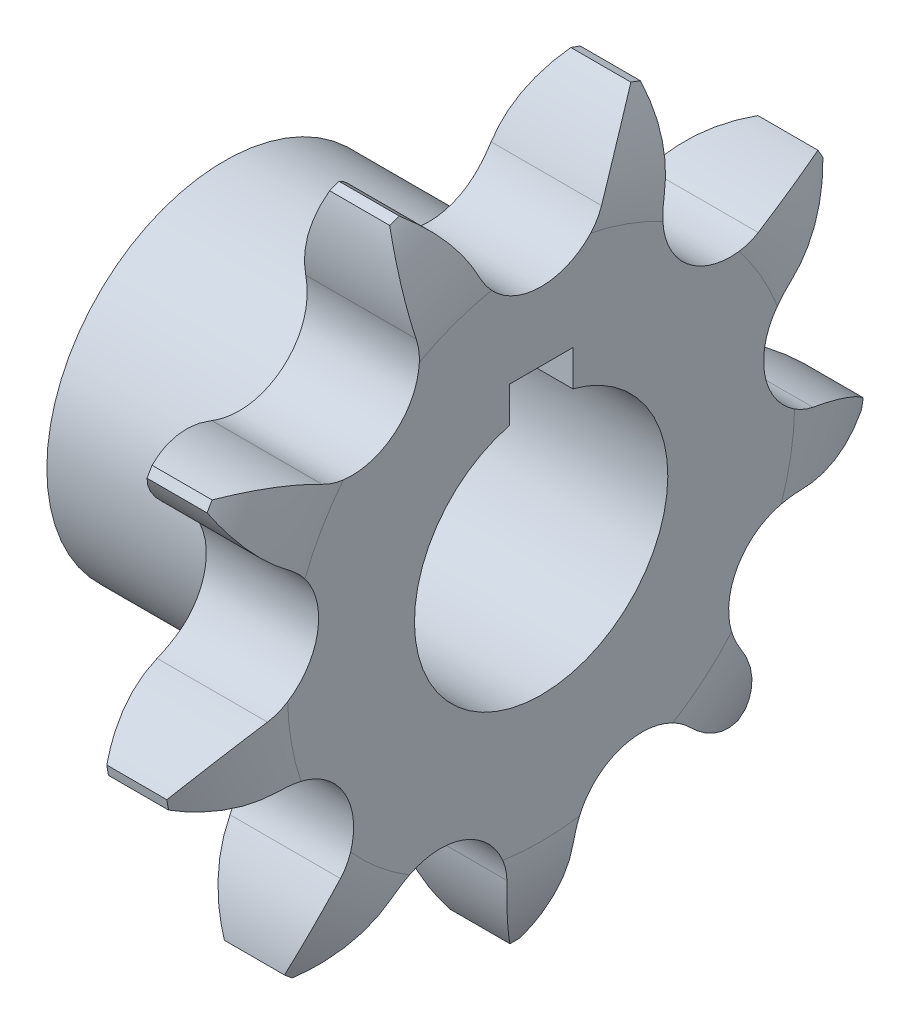
SolidWorks part; units mm, degrees
material "1.0503 (C45)"
ref_plane "Plane1" through (0, 0, 0) normal (0, 0, 1) x (1, 0, 0)
ref_plane "Plane2" through (0, 0, 0) normal (0, 1, 0) x (1, 0, 0)
ref_plane "Plane3" through (0, 0, 0) normal (1, 0, 0) x (0, 0, -1)
sketch "Clipboard" plane through (0, 0, 0) normal (0, 1, 0) x (1, 0, 0)
  line L0 (0, 0) -> (9.4077, -1.49)
  line L1 (-15, 0) -> (100, 0) construction
  line L2 (0, 0) -> (-0.8203, 0.9272)
  line L3 (0, 0) -> (-8.8973, 3.4006)
  line L4 (0, 0) -> (3.0618, 0.4849)
  line L5 (0, 0) -> (-20.613, -7.688)
  line L6 (0, 0) -> (-4.4098, -2.9753)
  line L7 (-0.8203, 0.9272) -> (20.8459, 4.7475)
  line L8 (-76.2, 38.1) -> (-73.9, 38.1)
  line L9 (-73.3242, 40.7328) -> (-72.926, 40.7699)
  line L10 (-73.4529, 9.1872) -> (-63.2129, 9.1872)
  circle A0 centre (0, 0) radius 3.175
  circle A1 centre (0, 0) radius 8.4097
  circle A2 centre (0, 0) radius 9
  dimension "Dr" = 6.35
  dimension "MHD" = 16.8193
  dimension "Hub_dia" = 18
  dimension "Num_teeth" = 9
  dimension "Pitch" = 9.525
  dimension "Width" = 3.1
  dimension "Side_relief" = 1.238
  dimension "Side_radius" = 9.525
  dimension "Overall_len" = 22
  dimension "Show_teeth" = 9
  dimension "Thickness" = 5.3196
  dimension "OAL" = 22.0005
  dimension "T_dim" = 2.3
  dimension "Fillet_rad" = 0.4
  dimension "Face_width" = 5.32
  dimension "Num_strands" = 1
  dimension "Transv_pitch" = 10.24
  dimension "Plate_wid" = 8.26
sketch "BasProSke" plane through (0, 0, 0) normal (0, 1, 0) x (1, 0, 0)
  line L0 (-10, 0) -> (60, 0) construction
  line L1 (0, 0) -> (0, 12.0069)
  line L2 (0, 0) -> (5.3196, 0)
  line L3 (5.3196, 0) -> (5.3196, 12.0069)
  line L4 (4.0816, 16.7027) -> (1.238, 16.7027)
  arc A0 (0, 12.0069) -> (1.238, 16.7027) centre (9.525, 12.0069) cw
  arc A1 (5.3196, 12.0069) -> (4.0816, 16.7027) centre (-4.2054, 12.0069) ccw
  dimension "Thickness" = 5.3196
  dimension "D1" = 9.525
  dimension "G1" = 1.238
  dimension "G2" = 1.238
  dimension "Diameter" = 33.4055
revolve "Base-Revolve" add sketch "BasProSke" angle 360 about L0
sketch "TooCutSke" plane through (0, 0, 0) normal (1, 0, 0) x (0, 0, -1)
  line L0 (0, 13.9564) -> (2.9063, 12.6011) construction
  line L1 (0, 0) -> (0, 107) construction
  line L2 (0, 13.9564) -> (-10, 13.9564) construction
  line L3 (0, 13.9564) -> (-2.9063, 12.6011) construction
  arc A0 (2.9063, 12.6011) -> (5.9941, 16.1247) centre (10.503, 9.0588) cw
  arc A1 (2.9063, 12.6011) -> (-2.9063, 12.6011) centre (0, 13.9564) cw
  arc A2 (-2.9063, 12.6011) -> (-5.9941, 16.1247) centre (-10.503, 9.0588) ccw
  arc A3 (5.9941, 16.1247) -> (-5.9941, 16.1247) centre (0, 0) ccw
  dimension "R1" = 3.2067
  dimension "R2" = 8.382
  dimension "Overcut" = 17.2027
  dimension "Seat_radius" = 13.9564
  dimension "X" = 130
extrude "ToothCut" cut sketch "TooCutSke" along normal through all
pattern_circular "TeethCuts" count 9 every 40 about axis through (-10, 0, 0) along (1, 0, 0) of "ToothCut"
sketch "HubNeaOneSke" plane through (0, 0, 0) normal (-1, 0, 0) x (0, 0, 1)
  circle A0 centre (0, 0) radius 8.4097
  dimension "Diameter" = 16.8193
extrude "HubNearOne" add sketch "HubNeaOneSke" along normal blind 16.6809
fillet "HubNearOneFillet" radius 0.4 1 edges at (0, 0, -8.4097)
sketch "HubNeaBotSke" plane through (0, 0, 0) normal (-1, 0, 0) x (0, 0, 1)
  circle A0 centre (0, 0) radius 8.4097
  dimension "Diameter" = 16.8193
extrude "HubNearBoth" [suppressed] add sketch "HubNeaBotSke" along normal blind 8.3404
fillet "HubNearBothFillet" [suppressed] radius 0.4
ref_plane "FarPln" through (5.3196, 0, 0) normal (1, 0, 0) x (0, 0, -1)
sketch "HubFarSke" plane through (5.3196, 0, 0) normal (1, 0, 0) x (0, 0, -1)
  circle A0 centre (0, 0) radius 8.4097
  dimension "Diameter" = 16.8193
extrude "HubFar" [suppressed] add sketch "HubFarSke" along normal blind 8.3404
fillet "HubFarFillet" [suppressed] radius 0.4
sketch "BorSke" plane through (0, 0, 0) normal (1, 0, 0) x (0, 0, -1)
  circle A0 centre (0, 0) radius 6
  dimension "Diameter" = 12
extrude "Bore" cut sketch "BorSke" along normal mid plane 44.001
sketch "KeySke" plane through (0, 0, 0) normal (1, 0, 0) x (0, 0, -1)
  line L0 (-2.5, 0) -> (-2.5, 8.3)
  line L1 (-2.5, 8.3) -> (2.5, 8.3)
  line L2 (2.5, 8.3) -> (2.5, 0)
  line L3 (0, 0) -> (0, 34) construction
  line L4 (-2.5, 0) -> (2.5, 0)
  dimension "Offset" = 8.3
  dimension "Width" = 5
extrude "Keyway" [suppressed] cut sketch "KeySke" along normal mid plane 44.001
pattern_circular "Keyway2" [suppressed] count 2 every 90 about axis through (-10, 0, 0) along (1, 0, 0)
sketch "Sketch1" plane through (5.3196, 0, 0) normal (1, 0, 0) x (0, 0, -1)
  line L0 (-1.5, 7.5) -> (1.5, 7.5)
  line L1 (-1.5, 7.5) -> (-1.5, 4.5)
  line L2 (1.5, 7.5) -> (1.5, 4.5)
  line L3 (-1.5, 4.5) -> (1.5, 4.5)
  line L4 (-1.5, 7.5) -> (1.5, 4.5) construction
  line L5 (1.5, 7.5) -> (-1.5, 4.5) construction
  line L6 (0, 0) -> (0, 6) construction
  circle A0 centre (0, 0) radius 6 construction
  point P1 (0, 6)
  dimension "D1" = 3
extrude "Cut-Extrude1" cut sketch "Sketch1" against normal through all
sketch "Sketch2" plane through (5.3196, 0, 0) normal (1, 0, 0) x (0, 0, -1)
  circle A0 centre (0, 0) radius 22.4786
extrude "Cut-Extrude2" cut sketch "Sketch2" against normal through all from offset 15 offset against normal yes
equation "' \"Pitch@Clipboard\" = 12.7"
equation "' \"Num_strands@Clipboard\" = 1"
equation "' \"Num_teeth@Clipboard\" = 9"
equation "' \"Hub_dia@Clipboard\" = 50"
equation "' \"Overall_len@Clipboard\" = 3"
equation "' \"Diameter@BorSke\" = 12"
equation "' \"T_dim@Clipboard\" = 1"
equation "' \"Width@KeySke\" = 2"
equation "' \"Dr@Clipboard\" = 8.51"
equation "' \"Face_width@Clipboard\" = 7.2"
equation "' \"Side_radius@Clipboard\" = 12.7"
equation "' \"Side_relief@Clipboard\" = 1.27"
equation "' \"Transv_pitch@Clipboard\" = 13.92"
equation "' \"Show_teeth@Clipboard\" = 9"
equation "' \"Fillet_rad@Clipboard\" = 0.6"
equation "' \"Plate_wid@Clipboard\" = 11.8"
equation "\"Num_teeth@Clipboard\" = int( \"Num_teeth@Clipboard\" )"
equation "\"Num_teeth@Clipboard\" = ((sgn( \"Num_teeth@Clipboard\" - 5.0)+1)*( \"Num_teeth@Clipboard\" - 5.0))/2 +5.0"
equation "\"Num_teeth@Clipboard\" = ((sgn( \"Num_teeth@Clipboard\" - 200.0)-1)*( \"Num_teeth@Clipboard\" - 200.0))/-2 +200.0"
equation "\"MHD@Clipboard\" = \"Pitch@Clipboard\" * (1.0 / tan(3.14159265 / \"Num_teeth@Clipboard\" )) - 1.04 * \"Plate_wid@Clipboard\" - 0.76"
equation "\"Thickness@Clipboard\"  = \"Face_width@Clipboard\" + (\"Num_strands@Clipboard\" - 1) * \"Transv_pitch@Clipboard\""
equation "\"OAL@Clipboard\" = \"Thickness@Clipboard\" + 2 * \"Fillet_rad@Clipboard\" + 1"
equation "\"MHD@Clipboard\" = ((sgn( \"MHD@Clipboard\" - \"Hub_dia@Clipboard\" )-1)*( \"MHD@Clipboard\" - \"Hub_dia@Clipboard\" ))/-2+ \"Hub_dia@Clipboard\""
equation "\"OAL@Clipboard\" = ((sgn( \"OAL@Clipboard\" - \"Overall_len@Clipboard\" )+1)*( \"OAL@Clipboard\" - \"Overall_len@Clipboard\" ))/2 + \"Overall_len@Clipboard\" + 0.0005"
equation "\"Num_teeth@TeethCuts\" = int( \"Show_teeth@Clipboard\" ) + 1"
equation "\"Num_teeth@TeethCuts\" = ((sgn( \"Num_teeth@TeethCuts\" - \"Num_teeth@Clipboard\" )-1)*( \"Num_teeth@TeethCuts\" - \"Num_teeth@Clipboard\" ))/-2+ \"Num_teeth@Clipboard\""
equation "\"Num_teeth@TeethCuts\" = ((sgn( \"Num_teeth@TeethCuts\" - 2.0)+1)*( \"Num_teeth@TeethCuts\" - 2.0))/2 +2.0"
equation "\"Angle@TeethCuts\" = 360.0 / \"Num_teeth@Clipboard\""
equation "\"Seat_radius@TooCutSke\" = ( \"Pitch@Clipboard\" / 2.0) / sin(3.14159265 / \"Num_teeth@Clipboard\" ) - \"Dr@Clipboard\" / 2.0 + \"Dr@Clipboard\" * 0.505"
equation "\"R1@TooCutSke\"  = \"Dr@Clipboard\" * 0.505"
equation "\"X@TooCutSke\" = 140.0 - (90.0 / \"Num_teeth@Clipboard\")"
equation "\"R2@TooCutSke\" = 0.12 * \"Dr@Clipboard\" * ( \"Num_teeth@Clipboard\" + 2.0)"
equation "\"Overcut@TooCutSke\" = 0.5 + 0.625 * \"Pitch@Clipboard\" - 0.5 * \"Dr@Clipboard\"  +  \"Pitch@Clipboard\" / 2.0 / sin(3.14159265 / \"Num_teeth@Clipboard\" )"
equation "\"Diameter@BasProSke\" = 2.0 * ( 0.625 * \"Pitch@Clipboard\" - 0.5 * \"Dr@Clipboard\"  +  \"Pitch@Clipboard\" / 2.0 / sin(3.14159265 / \"Num_teeth@Clipboard\" ))"
equation "\"Thickness@BasProSke\"  = \"Thickness@Clipboard\""
equation "\"G1@BasProSke\" =  \"Side_relief@Clipboard\""
equation "\"G2@BasProSke\" =  \"Side_relief@Clipboard\""
equation "\"D1@BasProSke\" =  \"Side_radius@Clipboard\""
equation "\"Diameter@HubNeaOneSke\" = \"MHD@Clipboard\""
equation "\"Length@HubNearOne\" = \"OAL@Clipboard\" - \"Thickness@BasProSke\""
equation "\"Diameter@HubNeaBotSke\" = \"MHD@Clipboard\""
equation "\"Length@HubNearBoth\" = ( \"OAL@Clipboard\" - \"Thickness@BasProSke\" ) / 2.0"
equation "\"D1@HubNearOneFillet\" = \"Fillet_rad@Clipboard\""
equation "\"D1@HubNearBothFillet\" = \"Fillet_rad@Clipboard\""
equation "\"Thickness@FarPln\" = \"Thickness@BasProSke\""
equation "\"Diameter@HubFarSke\" = \"MHD@Clipboard\""
equation "\"Length@HubFar\" = ( \"OAL@Clipboard\" - \"Thickness@BasProSke\" ) / 2.0"
equation "\"D1@HubFarFillet\" = \"Fillet_rad@Clipboard\""
equation "\"D1@Bore\" = \"OAL@Clipboard\" * 2.0"
equation "\"D1@Keyway\" = \"OAL@Clipboard\" * 2.0"
equation "\"Offset@KeySke\" = \"T_dim@Clipboard\" + \"Diameter@BorSke\" / 2.0"
